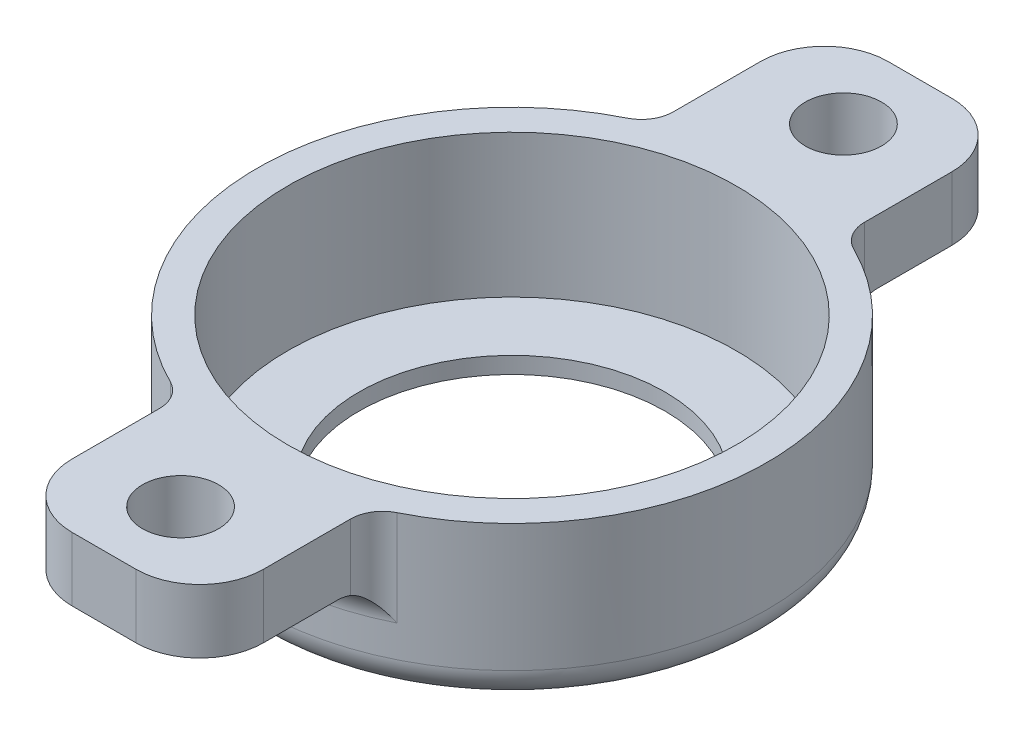
SolidWorks part; units mm, degrees
ref_plane "Front Plane" through (0, 0, 0) normal (0, 0, 1) x (1, 0, 0)
ref_plane "Top Plane" through (0, 0, 0) normal (0, 1, 0) x (1, 0, 0)
ref_plane "Right Plane" through (0, 0, 0) normal (1, 0, 0) x (0, 0, -1)
sketch "Sketch1" plane through (0, 0, 0) normal (0, 1, 0) x (1, 0, 0)
  circle A0 centre (0, 0) radius 12.7
  dimension "D1" = 25.4
extrude "Boss-Extrude1" add sketch "Sketch1" along normal blind 7.9375
sketch "Sketch3" plane through (0, 7.9375, 0) normal (0, 1, 0) x (1, 0, 0)
  circle A0 centre (0, 0) radius 7.62
  dimension "D1" = 15.24
extrude "Cut-Extrude2" cut sketch "Sketch3" against normal through all
sketch "Sketch4" plane through (0, 7.9375, 0) normal (0, 1, 0) x (1, 0, 0)
  circle A0 centre (0, 0) radius 11.176
  dimension "D1" = 22.352
extrude "Cut-Extrude3" cut sketch "Sketch4" against normal blind 7.112
sketch "Sketch5" plane through (0, 7.9375, 0) normal (0, 1, 0) x (1, 0, 0)
  line L0 (-4.7625, 11.7732) -> (-4.7625, 20.32)
  line L1 (-4.7625, 20.32) -> (4.7625, 20.32)
  line L2 (4.7625, 20.32) -> (4.7625, 11.7732)
  circle A0 centre (0, 0) radius 12.7 construction
  arc A1 (4.7625, 11.7732) -> (-4.7625, 11.7732) centre (0, 0) ccw
  dimension "D1" = 9.525
  dimension "D2" = 4.7625
  dimension "D3" = 20.32
extrude "Boss-Extrude2" add sketch "Sketch5" against normal blind 3.175
sketch "Sketch6" plane through (0, 7.9375, 0) normal (0, 1, 0) x (1, 0, 0)
  circle A0 centre (0, 16.51) radius 1.9
  dimension "D1" = 3.8
  dimension "D2" = 16.51
extrude "Cut-Extrude4" cut sketch "Sketch6" against normal through all and the other way through all
fillet "Fillet1" radius 3.175 2 edges at (-4.7625, 6.35, -20.32) (4.7625, 6.35, -20.32)
pattern_circular "CirPattern1" count 2 over 360 about axis through (0, 0, 0) along (0, 1, 0) of "Fillet1", "Cut-Extrude4", "Boss-Extrude2"
fillet "Fillet2" radius 1.5875 7 edges at (-4.7625, 6.35, 11.7732) (4.7625, 6.35, 11.7732) (4.7625, 6.35, -11.7732) (-4.7625, 6.35, -11.7732) (0, 4.7625, 12.7) (0, 4.7625, -12.7) (0, 0, 12.7)
